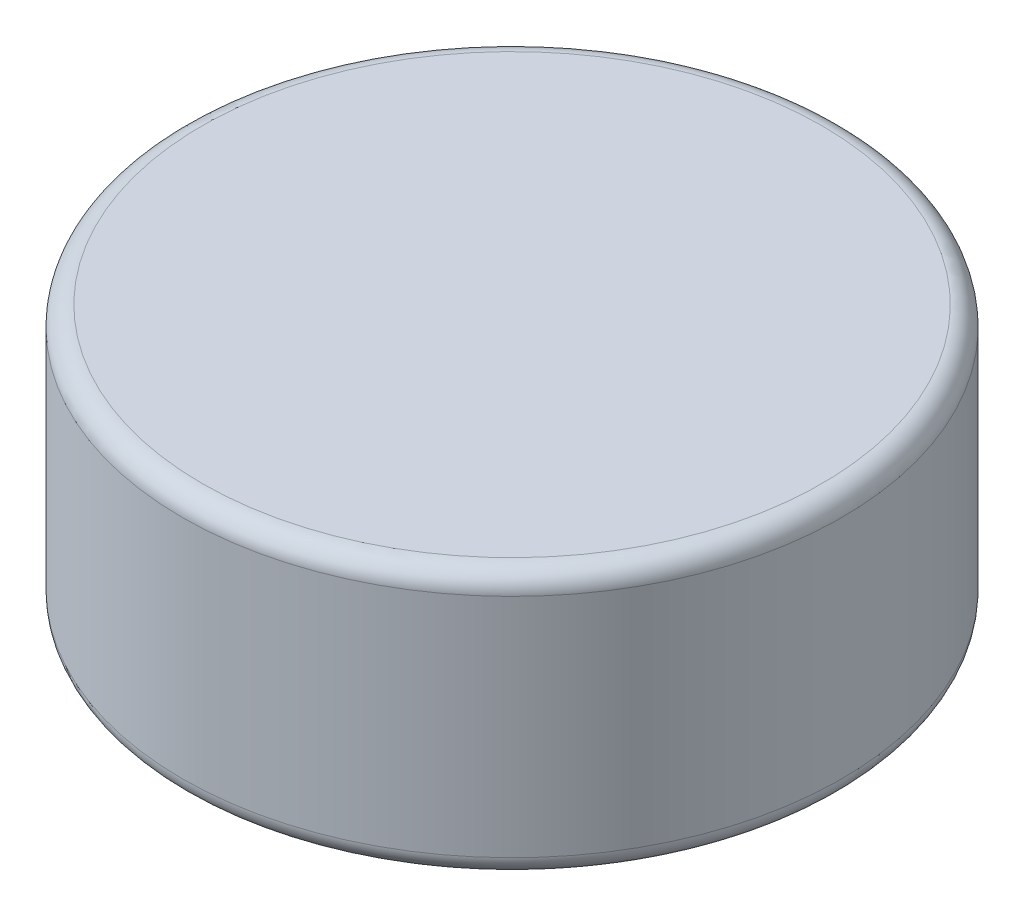
SolidWorks part; units mm, degrees
ref_plane "Plano frontal" through (0, 0, 0) normal (0, 0, 1) x (1, 0, 0)
ref_plane "Plano superior" through (0, 0, 0) normal (0, 1, 0) x (1, 0, 0)
ref_plane "Plano direito" through (0, 0, 0) normal (1, 0, 0) x (0, 0, -1)
sketch "Esboço1" plane through (0, 0, 0) normal (0, 1, 0) x (1, 0, 0)
  circle A0 centre (0, 0) radius 33.5
  dimension "D1" = 67
extrude "Ressalto-extrusão1" add sketch "Esboço1" along normal blind 27
fillet "Filete1" radius 2 2 edges at (0, 0, 33.5) (0, 27, 33.5)
sketch "Esboço2" plane through (0, 0, 0) normal (0, -1, 0) x (-1, 0, 0)
  circle A0 centre (0, 0) radius 5.75
  dimension "D1" = 11.5
extrude "Ressalto-extrusão2" add sketch "Esboço2" along normal blind 2
sketch "Esboço3" plane through (0, -2, 0) normal (0, -1, 0) x (1, 0, 0)
  circle A0 centre (0, 0) radius 3
  dimension "D1" = 6
extrude "Corte-extrusão1" cut sketch "Esboço3" against normal blind 5
